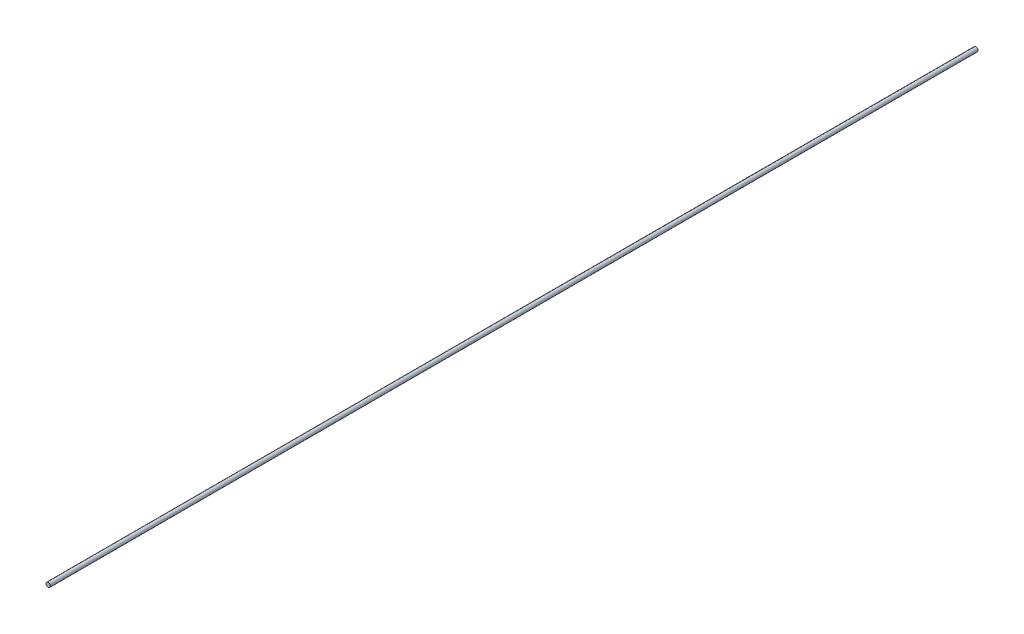
SolidWorks part; units mm, degrees
material "AISI 304"
ref_plane "Front Plane" through (0, 0, 0) normal (0, 0, 1) x (1, 0, 0)
ref_plane "Top Plane" through (0, 0, 0) normal (0, 1, 0) x (1, 0, 0)
ref_plane "Right Plane" through (0, 0, 0) normal (1, 0, 0) x (0, 0, -1)
sketch "Sketch1" plane through (0, 0, 0) normal (0, 0, 1) x (1, 0, 0)
  circle A0 centre (0, 0) radius 3
  dimension "D1" = 6
extrude "Boss-Extrude1" add sketch "Sketch1" along normal blind 1276.35
